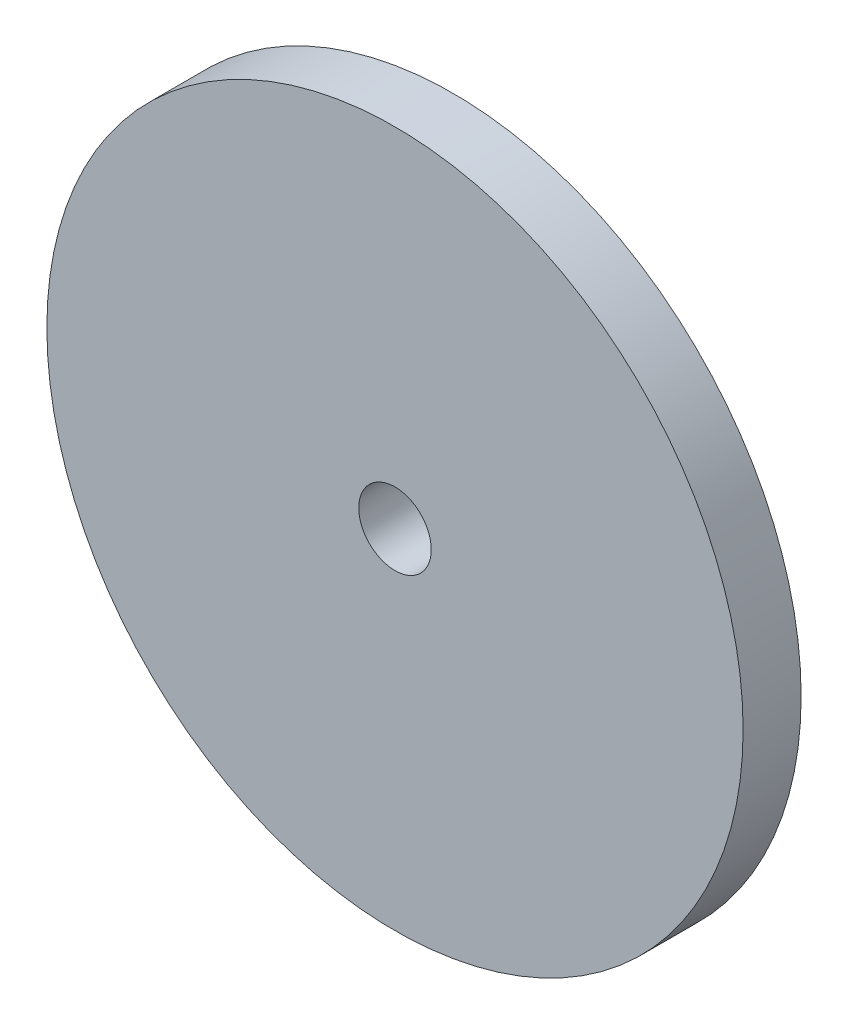
SolidWorks part; units mm, degrees
ref_plane "Front Plane" through (0, 0, 0) normal (0, 0, 1) x (1, 0, 0)
ref_plane "Top Plane" through (0, 0, 0) normal (0, 1, 0) x (1, 0, 0)
ref_plane "Right Plane" through (0, 0, 0) normal (1, 0, 0) x (0, 0, -1)
sketch "Sketch2" plane through (0, 0, 0) normal (0, 0, 1) x (1, 0, 0)
  circle A0 centre (0, 0) radius 3.175
  circle A1 centre (0, 0) radius 30.48
extrude "Boss-Extrude1" add sketch "Sketch2" along normal blind 5.08
